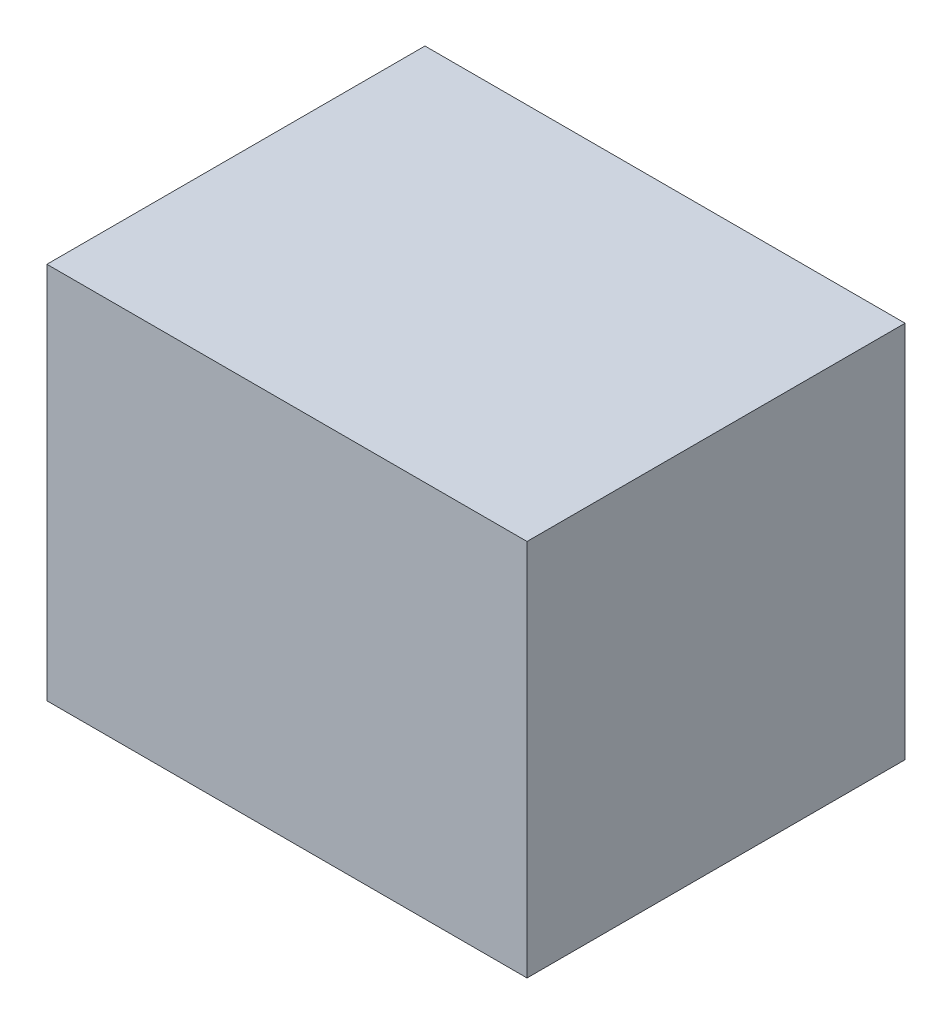
SolidWorks part; units mm, degrees
material "Oak"
ref_plane "Front Plane" through (0, 0, 0) normal (0, 0, 1) x (1, 0, 0)
ref_plane "Top Plane" through (0, 0, 0) normal (0, 1, 0) x (1, 0, 0)
ref_plane "Right Plane" through (0, 0, 0) normal (1, 0, 0) x (0, 0, -1)
sketch "Sketch1" plane through (0, 0, 0) normal (1, 0, 0) x (0, 0, -1)
  line L1 (10, 10) -> (-10, 10)
  line L2 (10, 10) -> (10, -10)
  line L3 (10, -10) -> (-10, -10)
  line L4 (-10, 10) -> (-10, -10)
  line L5 (10, 10) -> (-10, -10) construction
  line L6 (10, -10) -> (-10, 10) construction
  point P0 (0, 0)
  dimension "D1" = 20
  dimension "D2" = 20
extrude "Boss-Extrude1" add sketch "Sketch1" along normal mid plane 25.4
